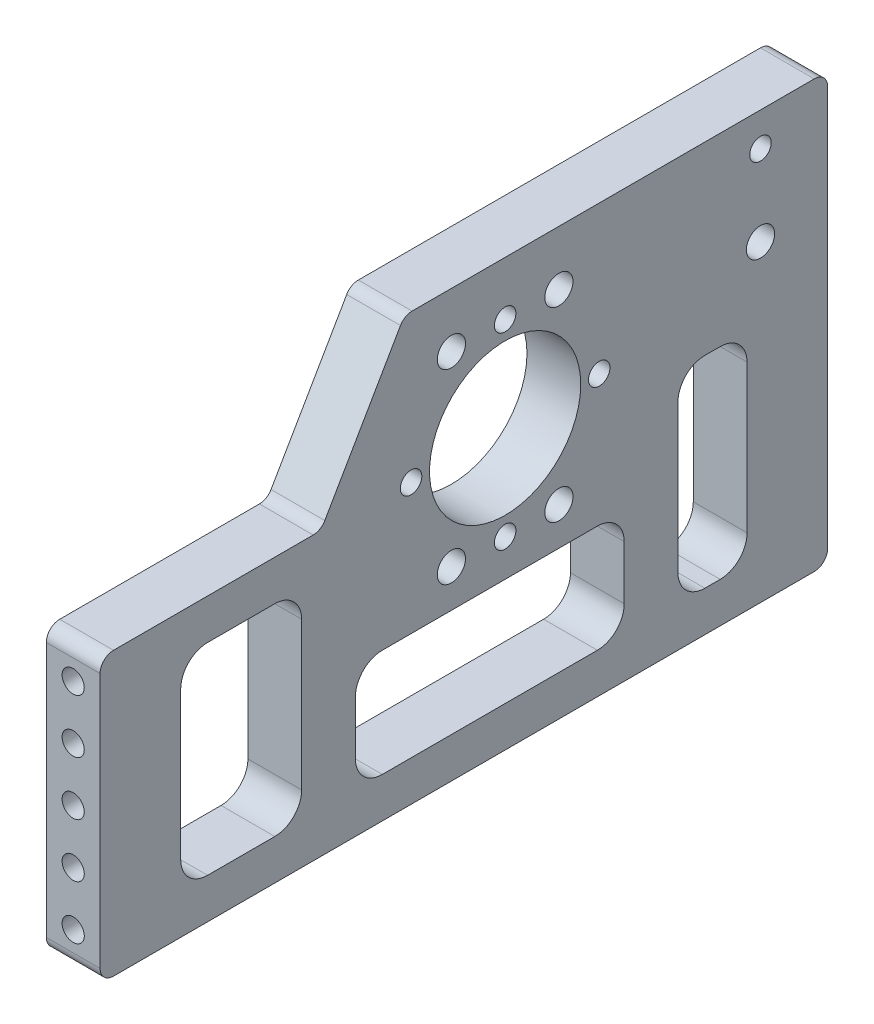
SolidWorks part; units mm, degrees
material "6061-T6 (SS)"
ref_plane "前视基准面" through (0, 0, 0) normal (0, 0, 1) x (1, 0, 0)
ref_plane "上视基准面" through (0, 0, 0) normal (0, 1, 0) x (1, 0, 0)
ref_plane "右视基准面" through (0, 0, 0) normal (1, 0, 0) x (0, 0, -1)
other "Configuration Table"
sketch "草图1" plane through (0, 0, 0) normal (1, 0, 0) x (0, 0, -1)
  line L0 (108.28, 42) -> (108.28, 63.5) construction
  line L1 (0, 0) -> (108.28, 0)
  line L2 (0, 0) -> (0, 42)
  line L3 (0, 42) -> (108.28, 42)
  line L4 (108.28, 0) -> (108.28, 42)
  line L5 (108.28, 63.5) -> (138.9157, 63.5) construction
  line L6 (60.28, 55.5) -> (60.28, 41.5) construction
  line L7 (60.28, 41.5) -> (68.28, 55.3564) construction
  line L8 (98.28, 58.5) -> (98.28, 46.5) construction
  line L9 (108.28, 42) -> (108.28, 63.5)
  line L10 (108.28, 63.5) -> (45.28, 63.5)
  line L11 (45.28, 63.5) -> (32.867, 42)
  circle A0 centre (60.28, 41.5) radius 22 construction
  circle A1 centre (60.28, 41.5) radius 29 construction
  circle A2 centre (98.28, 58.5) radius 5 construction
  circle A3 centre (98.28, 58.5) radius 1.6
  circle A4 centre (68.28, 55.3564) radius 2.1
  circle A5 centre (60.28, 55.5) radius 1.6
  circle A6 centre (76.28, 41.5) radius 2.1 construction
  circle A7 centre (68.28, 27.6436) radius 2.1
  circle A8 centre (52.28, 27.6436) radius 2.1
  circle A9 centre (44.28, 41.5) radius 2.1 construction
  circle A10 centre (52.28, 55.3564) radius 2.1
  circle A11 centre (74.28, 41.5) radius 1.6
  circle A12 centre (60.28, 27.5) radius 1.6
  circle A13 centre (46.28, 41.5) radius 1.6
  circle A14 centre (60.28, 41.5) radius 11.25
  circle A15 centre (98.28, 46.5) radius 2.1
  circle A16 centre (98.28, 58.5) radius 6 construction
  circle A17 centre (98.28, 46.5) radius 4.5 construction
  circle A18 centre (98.28, 38.5) radius 2.1 construction
  circle A19 centre (90.28, 46.5) radius 2.1 construction
  point P29 (60.28, 41.5)
  point P36 (60.28, 41.5)
  dimension "D4" = 44
  dimension "D5" = 58
  dimension "D6" = 10
  dimension "D7" = 10
  dimension "D8" = 3.2
  dimension "D9" = 48
  dimension "D10" = 30
  dimension "D11" = 4.2
  dimension "D14" = 3.2
  dimension "D16" = 22.5
  dimension "D17" = 4.2
  dimension "D19" = 12
  dimension "D20" = 9
  dimension "D24" = 8
  dimension "D1" = 108.28
  dimension "D2" = 42
  dimension "D3" = 21.5
  dimension "D12" = 16
  dimension "D13" = 14
  dimension "D18" = 12
  dimension "D21" = 60
  dimension "D22" = 15
  dimension "D23" = 2
  dimension "D25" = 2
  dimension "D15" = 6
extrude "凸台-拉伸1" add sketch "草图1" along normal blind 8 contours A14 L3 A13 L2 L1 L4 A11 A12 A8 A7 | A14 L3 A11 L9 L10 L11 A13 A15 A10 A5 A4 A3
sketch "草图2" plane through (0, 0, 0) normal (0, 0, 1) x (1, 0, 0)
  line L0 (0, 21) -> (8, 21) construction
  line L1 (0, 0) -> (0, 42) construction
  line L2 (8, 0) -> (8, 42) construction
  circle A0 centre (4, 21) radius 1.65
  circle A1 centre (4, 29) radius 1.65
  circle A2 centre (4, 37) radius 1.65
  circle A3 centre (4, 5) radius 1.65
  circle A4 centre (4, 13) radius 1.65
  dimension "D1" = 3.3
  dimension "D2" = 3
extrude "切除-拉伸1" cut sketch "草图2" against normal blind 10
ref_plane "基准面1" through (0, 0, -54.14) normal (0, 0, 1) x (1, 0, 0)
mirror "镜向1" about plane through (0, 0, -54.14) normal (0, 0, 1) of "切除-拉伸1"
sketch "草图3" plane through (8, 0, 0) normal (1, 0, 0) x (0, 0, -1)
  line L6 (0, 0) -> (108.28, 0) construction
  line L7 (12, 36) -> (30, 36)
  line L8 (12, 36) -> (12, 6)
  line L9 (12, 6) -> (30, 6)
  line L10 (30, 36) -> (30, 6)
  line L11 (38, 22) -> (78, 22)
  line L12 (38, 22) -> (38, 6)
  line L13 (38, 6) -> (78, 6)
  line L14 (78, 22) -> (78, 6)
  line L15 (86, 36) -> (96.28, 36)
  line L16 (86, 36) -> (86, 6)
  line L17 (86, 6) -> (96.28, 6)
  line L24 (96.28, 36) -> (96.28, 6)
  line L25 (0, 42) -> (32.867, 42) construction
  line L26 (0, 0) -> (0, 42) construction
  line L27 (108.28, 0) -> (108.28, 63.5) construction
  dimension "D1" = 18
  dimension "D2" = 6
  dimension "D3" = 6
  dimension "D4" = 12
  dimension "D5" = 8
  dimension "D6" = 16
  dimension "D7" = 8
  dimension "D8" = 40
  dimension "D9" = 12
extrude "切除-拉伸2" cut sketch "草图3" against normal blind 10
fillet "圆角1" radius 4 12 edges at (4, 36, -96.28) (4, 6, -96.28) (4, 6, -86) (4, 36, -86) (4, 22, -78) (4, 6, -78) (4, 6, -38) (4, 22, -38) (4, 36, -30) (4, 6, -30) (4, 6, -12) (4, 36, -12)
fillet "圆角2" radius 2 6 edges at (4, 0, -108.28) (4, 0, 0) (4, 42, -32.867) (4, 63.5, -45.28) (4, 63.5, -108.28) (4, 42, 0)
